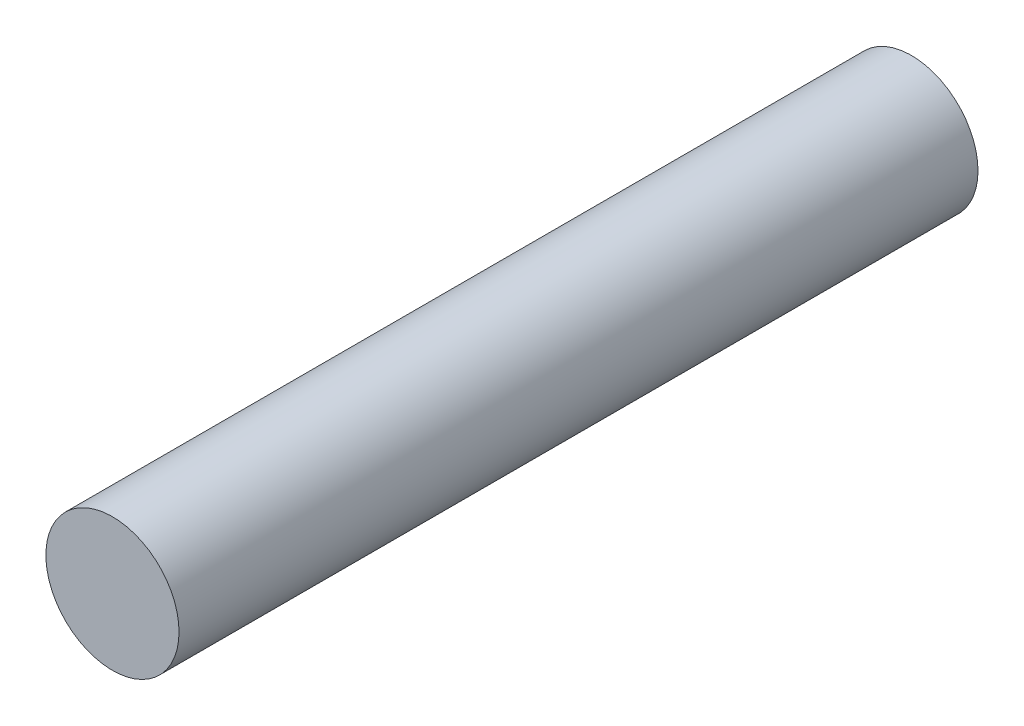
SolidWorks part; units mm, degrees
ref_plane "前视基准面" through (0, 0, 0) normal (0, 0, 1) x (1, 0, 0)
ref_plane "上视基准面" through (0, 0, 0) normal (0, 1, 0) x (1, 0, 0)
ref_plane "右视基准面" through (0, 0, 0) normal (1, 0, 0) x (0, 0, -1)
sketch "草图1" plane through (0, 0, 0) normal (0, 0, 1) x (1, 0, 0)
  circle A0 centre (0, 0) radius 25
  dimension "D1" = 50
extrude "凸台-拉伸1" add sketch "草图1" along normal blind 300
